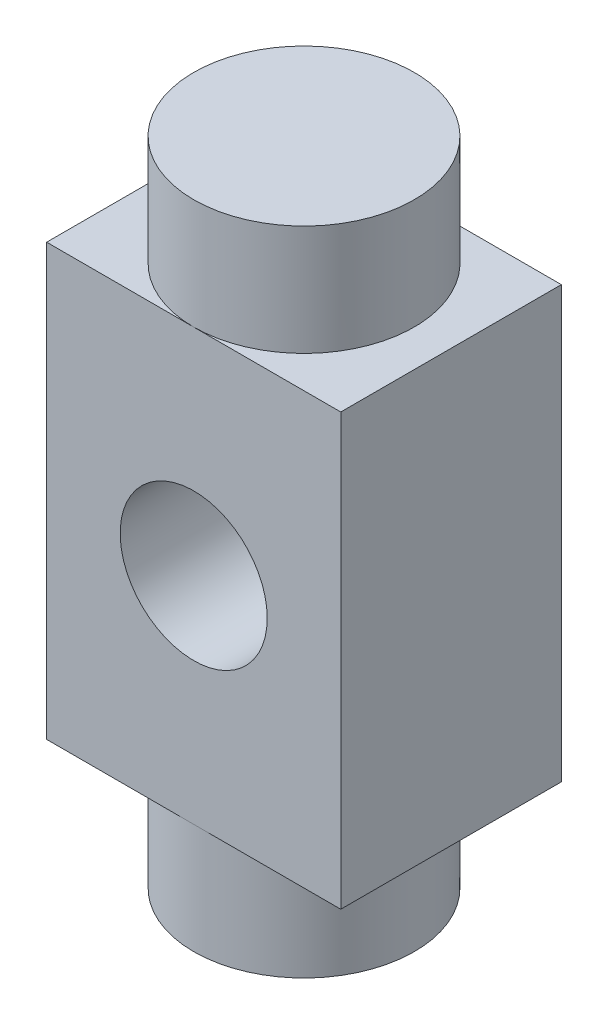
SolidWorks part; units mm, degrees
ref_plane "前视基准面" through (0, 0, 0) normal (0, 0, 1) x (1, 0, 0)
ref_plane "上视基准面" through (0, 0, 0) normal (0, 1, 0) x (1, 0, 0)
ref_plane "右视基准面" through (0, 0, 0) normal (1, 0, 0) x (0, 0, -1)
sketch "草图1" plane through (0, 0, 0) normal (0, 0, 1) x (1, 0, 0)
  line L0 (-2, 2.9284) -> (2, 2.9284)
  line L1 (2, 2.9284) -> (2, -2.9284)
  line L2 (2, -2.9284) -> (-2, -2.9284)
  line L3 (-2, -2.9284) -> (-2, 2.9284)
  circle A0 centre (0, 0) radius 1
extrude "凸台-拉伸1" add sketch "草图1" along normal blind 3
sketch "草图2" plane through (0, 2.9284, 0) normal (0, 1, 0) x (1, 0, 0)
  circle A0 centre (0, -1.5) radius 1.5
extrude "凸台-拉伸2" add sketch "草图2" along normal blind 1.5
mirror "镜向1" about plane through (0, 0, 0) normal (0, 1, 0) of "凸台-拉伸2"
